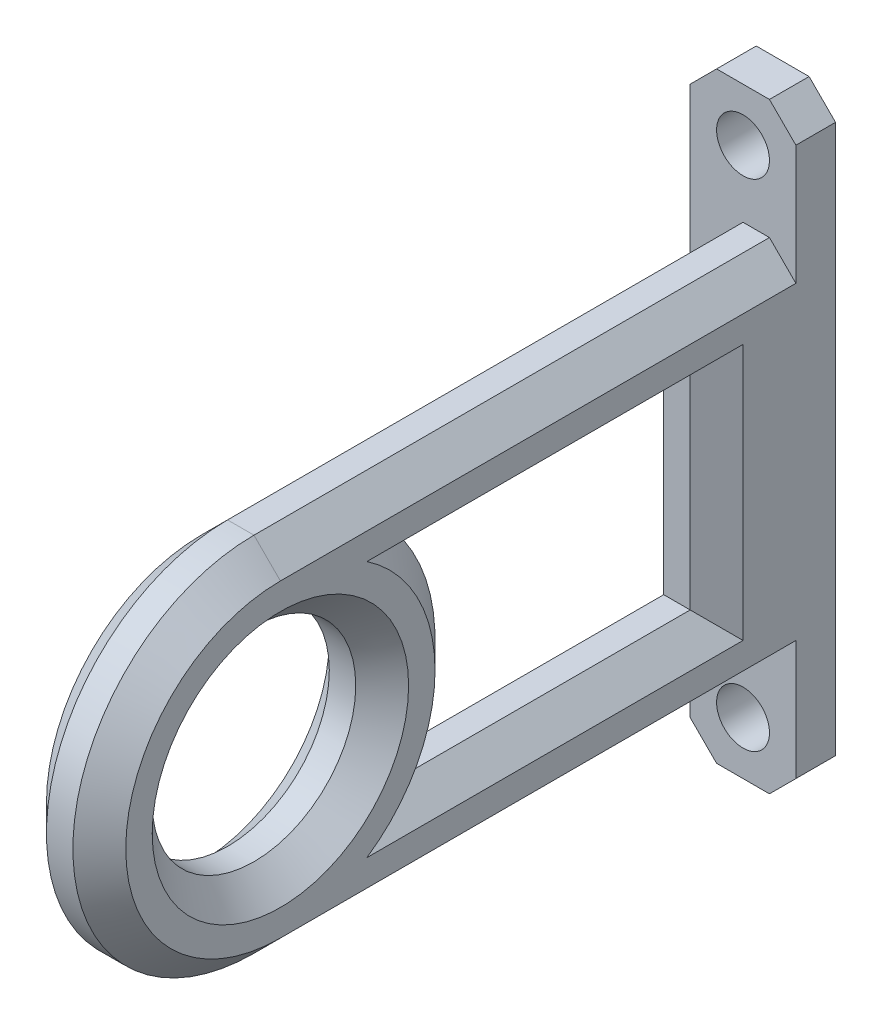
SolidWorks part; units mm, degrees
ref_plane "Front Plane" through (0, 0, 0) normal (0, 0, 1) x (1, 0, 0)
ref_plane "Top Plane" through (0, 0, 0) normal (0, 1, 0) x (1, 0, 0)
ref_plane "Right Plane" through (0, 0, 0) normal (1, 0, 0) x (0, 0, -1)
sketch "Sketch1" plane through (0, 0, 0) normal (1, 0, 0) x (0, 0, -1)
  line L0 (0, 13.7) -> (39, 13.7)
  line L1 (0, -13.7) -> (39, -13.7)
  line L2 (39, -13.7) -> (39, 13.7)
  line L3 (11.3314, 7.7) -> (33, 7.7)
  line L4 (33, -7.7) -> (33, 7.7)
  line L5 (11.3314, -7.7) -> (33, -7.7)
  line L6 (0, 7.7) -> (33, 7.7) construction
  line L7 (0, -7.7) -> (33, -7.7) construction
  line L9 (39, 20.75) -> (39, -20.75) construction
  arc A0 (0, 13.7) -> (0, -13.7) centre (0, 0) ccw
  arc A1 (0, 13.7) -> (0, -13.7) centre (0, 0) cw construction
  arc A2 (11.3314, -7.7) -> (11.3314, 7.7) centre (0, 0) ccw
  circle A3 centre (0, 0) radius 7.7
  circle A4 centre (0, 0) radius 7.5 construction
  dimension "D1" = 6
  dimension "D2" = 6
  dimension "D3" = 0.2
extrude "Boss-Extrude1" add sketch "Sketch1" along normal blind 6
chamfer "Chamfer1" distance 2 angle 45 16 edges at (0, -13.7, -19.5) (0, 0, 13.7) (0, 13.7, -19.5) (0, 0, -13.7) (0, 0, -33) (0, 7.7, -22.1657) (6, 0, -13.7) (6, -7.7, -22.1657) (6, 0, -33) (6, 7.7, -22.1657) (6, -13.7, -19.5) (6, 0, 13.7) (6, 13.7, -19.5) (0, -7.7, -22.1657) (6, 0, -7.7) (0, 0, -7.7)
sketch "Sketch4" plane through (0, 0, -39) normal (0, 0, -1) x (-1, 0, 0)
  line L0 (-6, -22.75) -> (-6, 22.75)
  line L1 (-6, -11.7) -> (-6, 11.7) construction
  line L2 (-6, 22.75) -> (2, 22.75)
  line L3 (2, 22.75) -> (2, -22.75)
  line L4 (2, 0) -> (-6, 0) construction
  line L7 (-6, -22.75) -> (2, -22.75)
  line L8 (-59, -22.75) -> (-39, -22.75) construction
  circle A0 centre (-2, 18.75) radius 2
  circle A1 centre (-2, -18.75) radius 2
  point P9 (-2, 22.75)
  dimension "D1" = 4
  dimension "D2" = 8
  dimension "D3" = 4
extrude "Boss-Extrude2" add sketch "Sketch4" along normal blind 3
chamfer "Chamfer2" distance 2 angle 45 4 edges at (6, -22.75, -40.5) (-2, -22.75, -40.5) (6, 22.75, -40.5) (-2, 22.75, -40.5)
